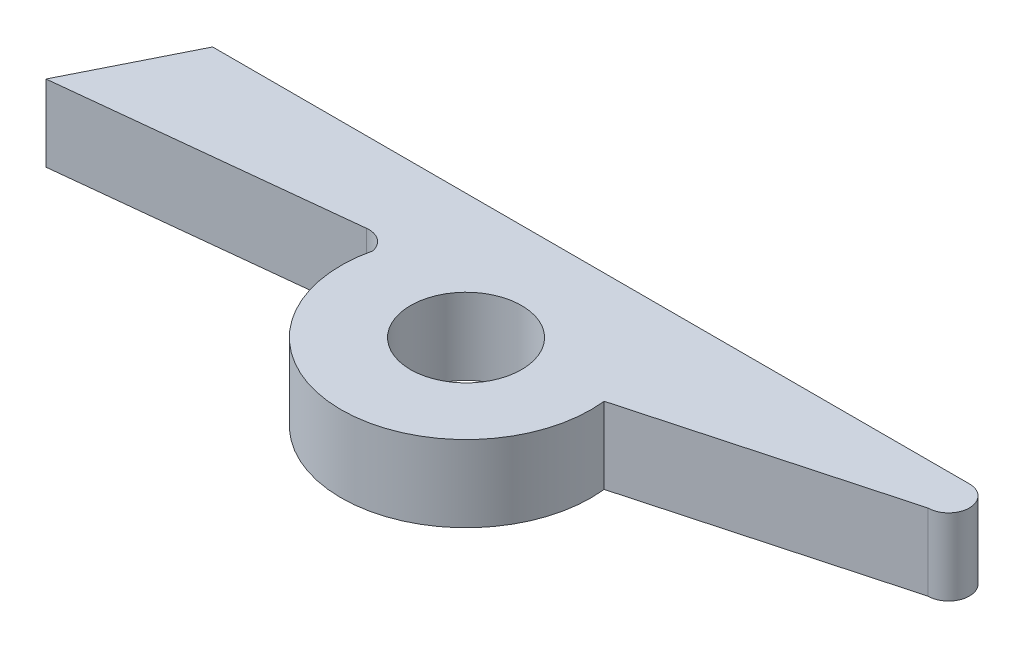
SolidWorks part; units mm, degrees
ref_plane "Piano frontale" through (0, 0, 0) normal (0, 0, 1) x (1, 0, 0)
ref_plane "Piano superiore" through (0, 0, 0) normal (0, 1, 0) x (1, 0, 0)
ref_plane "Piano destro" through (0, 0, 0) normal (1, 0, 0) x (0, 0, -1)
sketch "Schizzo1" plane through (0, 0, 0) normal (0, 1, 0) x (1, 0, 0)
  line L0 (-10.3895, 3.2315) -> (-31.25, 1)
  line L1 (-31.25, 1) -> (-27.25, 9)
  line L2 (-27.25, 9) -> (27.25, 9)
  line L3 (27.25, 6) -> (8.94, 1)
  circle A0 centre (0, 0) radius 4
  arc A1 (-8.7629, 2.0523) -> (8.9441, 1.0011) centre (0, 0) ccw
  arc A2 (-8.7629, 2.0523) -> (-10.3895, 3.2315) centre (-10.23, 1.74) ccw
  arc A3 (27.25, 6) -> (27.25, 9) centre (27.25, 7.5) ccw
  point P12 (0, 0)
  point P13 (0, 9)
  point P16 (-8.73, -0.24)
  point P17 (-8.7198, 2.2282)
  point P18 (-10.23, 1)
  point P19 (0, 0)
  point P20 (-11.5501, 2.4524)
  dimension "D1" = 8
  dimension "D2" = 18
  dimension "D4" = 3
  dimension "D10" = 3
  dimension "D3" = 8
  dimension "D5" = 21.02
  dimension "D6" = 4
  dimension "D7" = 9
  dimension "D8" = 1.74
  dimension "D9" = 54.5
  dimension "D11" = 8
  dimension "D12" = 8.94
extrude "Estrusione-Estrusione1" add sketch "Schizzo1" along normal blind 5.5
